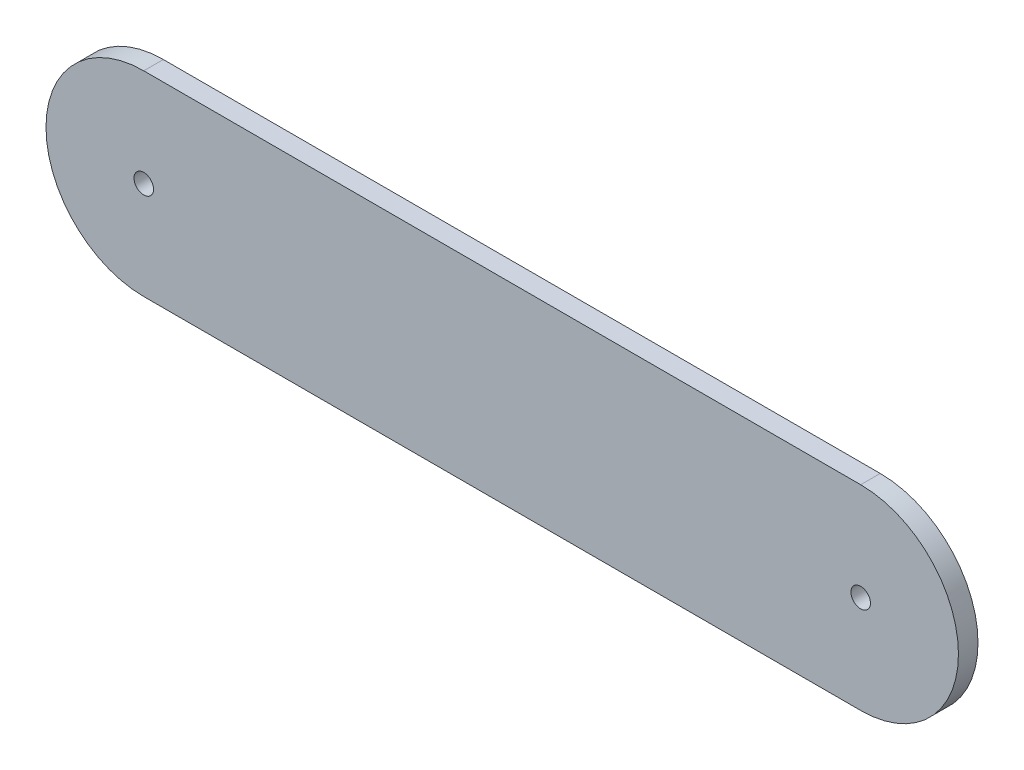
SolidWorks part; units mm, degrees
ref_plane "Front Plane" through (0, 0, 0) normal (0, 0, 1) x (1, 0, 0)
ref_plane "Top Plane" through (0, 0, 0) normal (0, 1, 0) x (1, 0, 0)
ref_plane "Right Plane" through (0, 0, 0) normal (1, 0, 0) x (0, 0, -1)
sketch "Sketch1" plane through (0, 0, 0) normal (0, 0, 1) x (1, 0, 0)
  line L0 (-132.3646, 29.7635) -> (-22.3646, 29.7635)
  line L2 (-22.3646, -0.2365) -> (-132.3646, -0.2365)
  arc A0 (-22.3646, -0.2365) -> (-22.3646, 29.7635) centre (-22.3646, 14.7635) ccw
  arc A1 (-132.3646, 29.7635) -> (-132.3646, -0.2365) centre (-132.3646, 14.7635) ccw
  circle A2 centre (-22.3646, 14.7635) radius 1.5
  circle A3 centre (-132.3646, 14.7635) radius 1.5
extrude "Boss-Extrude1" add sketch "Sketch1" along normal blind 3
